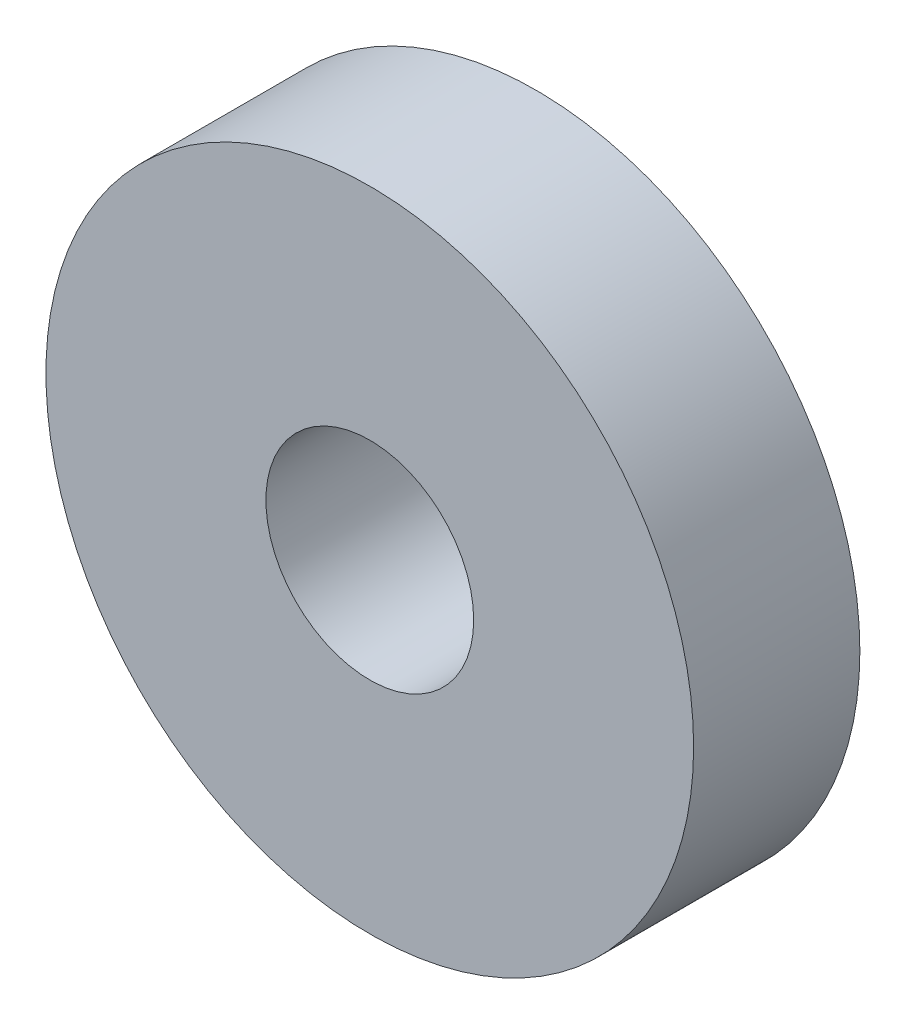
SolidWorks part; units mm, degrees
material "Custom Plastic"
ref_plane "Front Plane" through (0, 0, 0) normal (0, 0, 1) x (1, 0, 0)
ref_plane "Top Plane" through (0, 0, 0) normal (0, 1, 0) x (1, 0, 0)
ref_plane "Right Plane" through (0, 0, 0) normal (1, 0, 0) x (0, 0, -1)
sketch "Sketch1" plane through (0, 0, 0) normal (0, 0, 1) x (1, 0, 0)
  circle A0 centre (0, 0) radius 12.5
  circle A1 centre (0, 0) radius 38.9636
  dimension "D1" = 25
  dimension "D2" = 77.9272
extrude "Boss-Extrude1" add sketch "Sketch1" along normal blind 20
